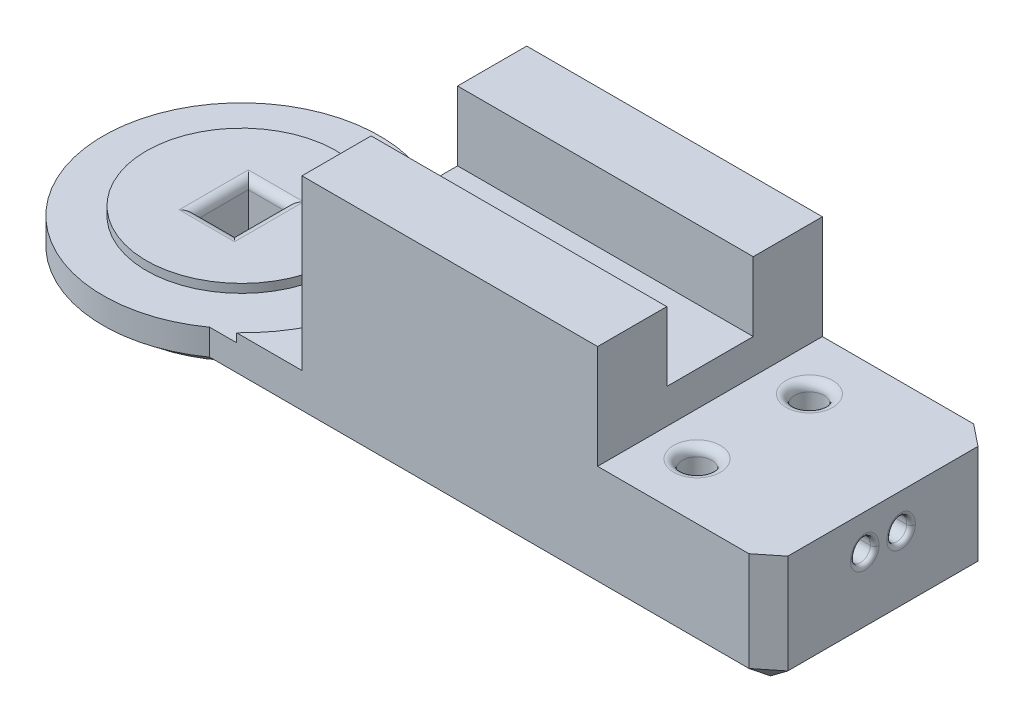
SolidWorks part; units mm, degrees
ref_plane "Front Plane" through (0, 0, 0) normal (0, 0, 1) x (1, 0, 0)
ref_plane "Top Plane" through (0, 0, 0) normal (0, 1, 0) x (1, 0, 0)
ref_plane "Right Plane" through (0, 0, 0) normal (1, 0, 0) x (0, 0, -1)
sketch "Sketch1" plane through (0, 0, 0) normal (0, 1, 0) x (1, 0, 0)
  line L0 (-1.1, 1.0198) -> (-1.1, -1.0198)
  line L1 (1.1, 1.0198) -> (1.1, -1.0198)
  line L2 (-998.0463, -6.5) -> (49001.9537, -6.5) construction
  line L3 (-998.5569, 6.5) -> (49001.4431, 6.5) construction
  line L4 (32.1, -1002.9744) -> (32.1, 48997.0256) construction
  line L5 (4.6637, 6.5) -> (32.1, 6.5)
  line L6 (32.1, 6.5) -> (32.1, -6.5)
  line L7 (32.1, -6.5) -> (4.6637, -6.5)
  line L8 (0.887, 1.2096) -> (1.1, 1.5) construction
  line L9 (-1.1, 1.5) -> (1.1, 1.5)
  line L10 (-1.1, 1.5) -> (-1.1, -1.5)
  line L11 (-1.1, -1.5) -> (1.1, -1.5)
  line L12 (1.1, 1.5) -> (1.1, -1.5)
  line L13 (-0.887, 1.2096) -> (1.1, -1.5) construction
  line L14 (-1.1, -1.5) -> (0.887, 1.2096) construction
  line L15 (-1.1, 1.5) -> (-0.887, 1.2096) construction
  arc A0 (-1.1, -1.0198) -> (-0.887, -1.2096) centre (0, 0) ccw construction
  arc A1 (-1.1, 1.0198) -> (-1.1, -1.0198) centre (0, 0) ccw construction
  arc A2 (1.1, -1.0198) -> (1.1, 1.0198) centre (0, 0) ccw construction
  arc A3 (-0.887, 1.2096) -> (-1.1, 1.0198) centre (0, 0) ccw construction
  arc A4 (4.6637, 6.5) -> (4.6637, -6.5) centre (0, 0) ccw
  arc A5 (4.6637, -6.5) -> (4.6637, 6.5) centre (0, 0) ccw construction
  arc A6 (-0.887, -1.2096) -> (0, -1.5) centre (0, 0) ccw construction
  arc A7 (0.887, -1.2096) -> (1.1, -1.0198) centre (0, 0) ccw construction
  arc A8 (0, -1.5) -> (0.887, -1.2096) centre (0, 0) ccw construction
  arc A9 (1.1, 1.0198) -> (0.887, 1.2096) centre (0, 0) ccw construction
  arc A10 (0.887, 1.2096) -> (0, 1.5) centre (0, 0) ccw construction
  arc A11 (0, 1.5) -> (-0.887, 1.2096) centre (0, 0) ccw construction
  dimension "D1" = 3
  dimension "D4" = 16
  dimension "D2" = 1.1
  dimension "D3" = 1.1
  dimension "D5" = 6.5
  dimension "D6" = 6.5
  dimension "D7" = 32.1
extrude "Boss-Extrude1" add sketch "Sketch1" against normal blind 3 contours L5 A4 L7 L6 L9 L12 L1 L11 L10 L0
sketch "Sketch2" plane through (0, 0, 0) normal (0, 1, 0) x (1, 0, 0)
  circle A0 centre (0, 0) radius 9
  circle A1 centre (0, 0) radius 5.5
  dimension "D1" = 18
  dimension "D2" = 3.5
extrude "Cut-Extrude1" cut sketch "Sketch2" against normal blind 0.5
sketch "Sketch3" plane through (0, 0, 0) normal (0, 1, 0) x (1, 0, 0)
  line L1 (32.1, 6.5) -> (10, 6.5)
  line L2 (32.1, 6.5) -> (32.1, -6.5)
  line L3 (32.1, -6.5) -> (10, -6.5)
  line L4 (10, 6.5) -> (10, -6.5)
  line L5 (32.1, -6.5) -> (6.2249, -6.5) construction
  dimension "D1" = 10
extrude "Boss-Extrude2" add sketch "Sketch3" along normal blind 3.75
sketch "Sketch4" plane through (0, -3, 0) normal (0, -1, 0) x (1, 0, 0)
  line L0 (27.1, 6.5) -> (27.1, -6.5) construction
  line L3 (29.6, 6.5) -> (29.6, -6.5) construction
  line L5 (27.1, 6.5) -> (32.1, 0) construction
  line L6 (32.1, 0) -> (27.1, -6.5) construction
  line L7 (32.1, -6.5) -> (32.1, 6.5) construction
  line L8 (32.1, 6.5) -> (4.6637, 6.5) construction
  line L9 (4.6637, -6.5) -> (32.1, -6.5) construction
  circle A0 centre (29.6, 3.25) radius 0.85
  circle A1 centre (29.6, -3.25) radius 0.85
  dimension "D3" = 1.7
  dimension "D4" = 1.7
  dimension "D1" = 2.5
  dimension "D2" = 2.5
extrude "Cut-Extrude2" cut sketch "Sketch4" against normal through all both and the other way through all
sketch "Sketch5" plane through (0, -3, 0) normal (0, -1, 0) x (1, 0, 0)
  line L0 (32.1, -6.5) -> (37.1, -6.5)
  line L1 (32.1, 6.5) -> (37.1, 6.5)
  line L2 (37.1, 6.5) -> (37.1, -6.5)
  line L3 (32.1, 6.5) -> (32.1, -6.5)
  dimension "D1" = 5
extrude "Boss-Extrude3" add sketch "Sketch5" against normal up to vertex (11.6 mm away)
chamfer "Chamfer1" distance 1 distance2 1.25 6 edges at (37.1, -3, 0) (37.1, 0.375, -6.5) (37.1, 0.375, 6.5) (-8, -3, 0) (20.8818, -3, -6.5) (20.8818, -3, 6.5)
fillet "Fillet1" radius 0.5 12 edges at (30.45, 3.75, -3.25) (29.6, -3, -2.4) (30.45, 3.75, 3.25) (29.6, -3, 4.1) (0, -3, -1.5) (-1.1, -3, 0) (0, -3, 1.5) (1.1, -3, 0) (-1.1, 0, 0) (0, 0, -1.5) (0, 0, 1.5) (1.1, 0, 0)
sketch "Sketch6" plane through (10, 0, 0) normal (-1, 0, 0) x (0, 0, 1)
  line L0 (6.5, 1.65) -> (-6.5, 1.65) construction
  line L4 (-6.5, 0) -> (6.5, 0) construction
  arc A0 (0.475, 1.65) -> (1.625, 1.65) centre (1.05, 1.65) ccw
  arc A1 (-1.625, 1.65) -> (-0.475, 1.65) centre (-1.05, 1.65) ccw
  arc A2 (1.625, 1.65) -> (0.475, 1.65) centre (1.05, 1.65) ccw construction
  arc A3 (-0.475, 1.65) -> (-1.625, 1.65) centre (-1.05, 1.65) ccw construction
  ellipse E0 centre (-1.05, 1.65) end of major axis (-1.05, 2.4) minor radius 0.575 (-0.475, 1.65) -> (-1.625, 1.65) ccw
  ellipse E1 centre (1.05, 1.65) end of major axis (1.05, 2.4) minor radius 0.575 (1.625, 1.65) -> (0.475, 1.65) ccw
  ellipse E2 centre (-1.05, 1.65) end of major axis (-1.05, 2.4) minor radius 0.575 (-1.625, 1.65) -> (-0.475, 1.65) ccw construction
  ellipse E3 centre (1.05, 1.65) end of major axis (1.05, 2.4) minor radius 0.575 (0.475, 1.65) -> (1.625, 1.65) ccw construction
  dimension "D1" = 1.15
  dimension "D2" = 1.15
  dimension "D3" = 2.1
  dimension "D4" = 1.05
  dimension "D5" = 1.65
  dimension "D6" = 0.75
  dimension "D7" = 0.75
extrude "Cut-Extrude3" cut sketch "Sketch6" against normal through all
fillet "Fillet2" radius 0.25 8 edges at (10, 1.075, -1.05) (37.1, 1.075, -1.05) (10, 1.075, 1.05) (37.1, 1.075, 1.05) (37.1, 2.4, -1.05) (10, 2.4, -1.05) (37.1, 2.4, 1.05) (10, 2.4, 1.05)
sketch "Sketch7" plane through (0, 3.75, 0) normal (0, 1, 0) x (1, 0, 0)
  line L0 (10, -6.5) -> (35.85, -6.5) construction
  line L1 (10, 6.5) -> (27.1, 6.5)
  line L2 (10, 6.5) -> (10, -6.5)
  line L3 (10, -6.5) -> (27.1, -6.5)
  line L4 (27.1, 6.5) -> (27.1, -6.5)
  dimension "D1" = 17.1
extrude "Boss-Extrude4" add sketch "Sketch7" along normal blind 6
sketch "Sketch8" plane through (0, 9.75, 0) normal (0, 1, 0) x (1, 0, 0)
  line L0 (10, 6.5) -> (10, -6.5) construction
  line L1 (10, -2.5) -> (27.1, -2.5)
  line L2 (10, -2.5) -> (10, 2.5)
  line L3 (10, 2.5) -> (27.1, 2.5)
  line L4 (27.1, -2.5) -> (27.1, 2.5)
  line L5 (27.1, -6.5) -> (27.1, 6.5) construction
  line L6 (10, -6.5) -> (27.1, -6.5) construction
  line L7 (27.1, 6.5) -> (10, 6.5) construction
  dimension "D1" = 4
  dimension "D2" = 4
extrude "Cut-Extrude4" cut sketch "Sketch8" against normal blind 4
